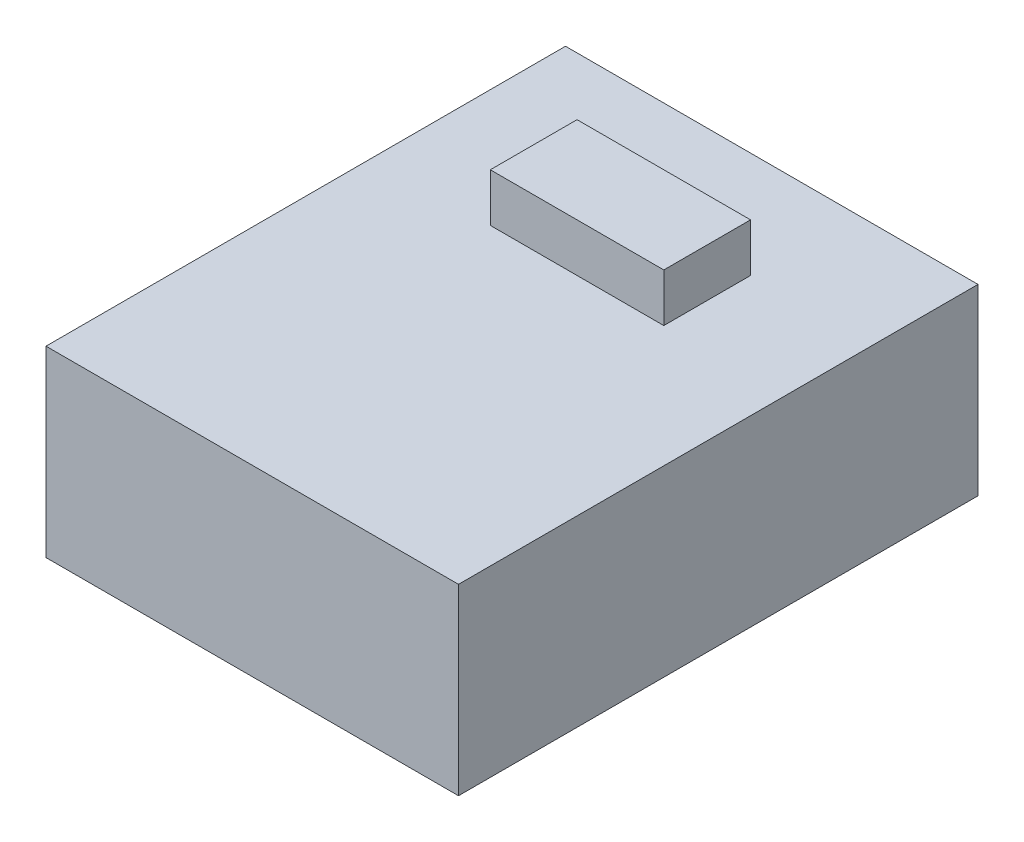
SolidWorks part; units mm, degrees
material "Epoxy, renforcé"
ref_plane "Plan de face" through (0, 0, 0) normal (0, 0, 1) x (1, 0, 0)
ref_plane "Plan de dessus" through (0, 0, 0) normal (0, 1, 0) x (1, 0, 0)
ref_plane "Plan de droite" through (0, 0, 0) normal (1, 0, 0) x (0, 0, -1)
sketch "Esquisse1" plane through (0, 0, 0) normal (0, 1, 0) x (1, 0, 0)
  line L1 (0, 0) -> (42.8, 0)
  line L2 (0, 0) -> (0, 53.9)
  line L3 (0, 53.9) -> (42.8, 53.9)
  line L4 (42.8, 0) -> (42.8, 53.9)
  dimension "D1" = 53.9
  dimension "D2" = 42.8
extrude "Boss.-Extru.1" add sketch "Esquisse1" along normal blind 19
sketch "Esquisse2" plane through (0, 19, 0) normal (0, 1, 0) x (1, 0, 0)
  line L0 (42.8, 53.9) -> (0, 53.9) construction
  line L1 (12.2, 42.9) -> (30.2, 42.9)
  line L2 (12.2, 42.9) -> (12.2, 33.9)
  line L3 (12.2, 33.9) -> (30.2, 33.9)
  line L4 (30.2, 42.9) -> (30.2, 33.9)
  line L5 (42.8, 0) -> (42.8, 53.9) construction
  dimension "D1" = 18
  dimension "D2" = 9
  dimension "D3" = 11
  dimension "D4" = 12.6
extrude "Boss.-Extru.2" add sketch "Esquisse2" along normal blind 5
